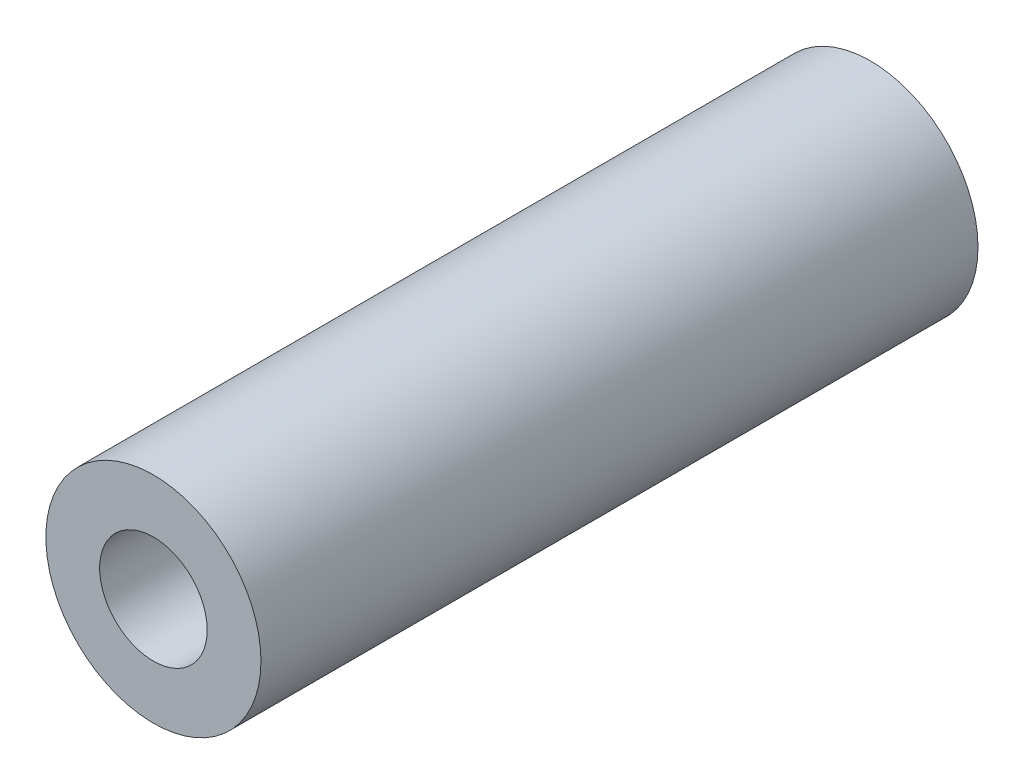
SolidWorks part; units mm, degrees
ref_plane "Front Plane" through (0, 0, 0) normal (0, 0, 1) x (1, 0, 0)
ref_plane "Top Plane" through (0, 0, 0) normal (0, 1, 0) x (1, 0, 0)
ref_plane "Right Plane" through (0, 0, 0) normal (1, 0, 0) x (0, 0, -1)
sketch "Sketch1" plane through (0, 0, 0) normal (0, 0, 1) x (1, 0, 0)
  circle A0 centre (0, 0) radius 4.5
  circle A1 centre (0, 0) radius 9
  dimension "D1" = 9
  dimension "D2" = 18
extrude "Boss-Extrude1" add sketch "Sketch1" along normal blind 60 contours A0 | A1
